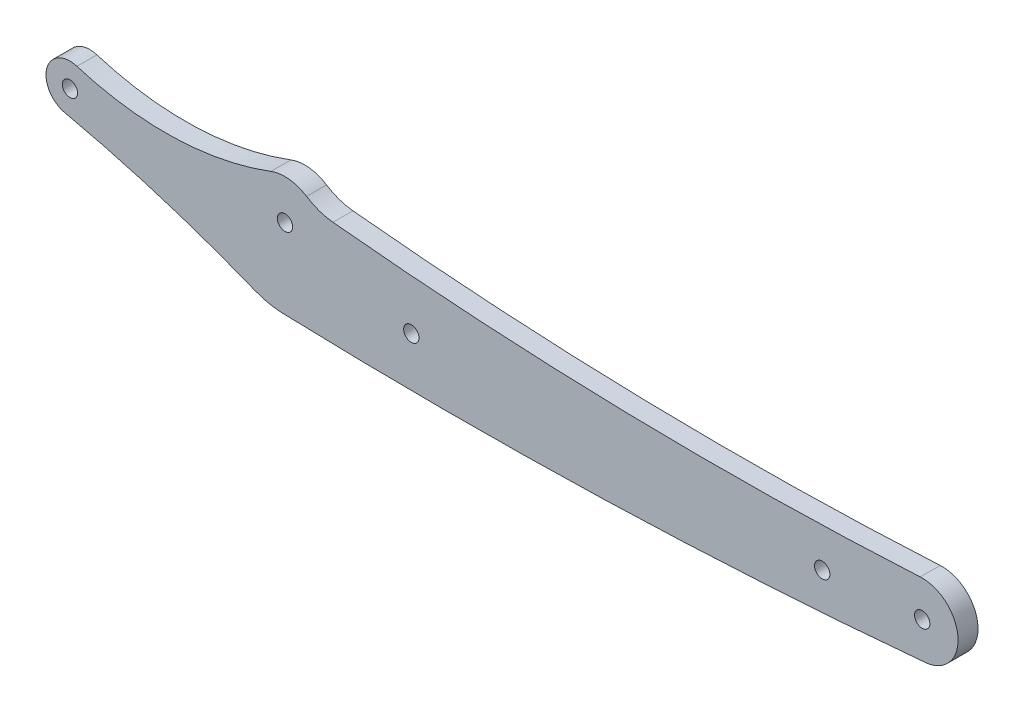
SolidWorks part; units mm, degrees
ref_plane "Plan de face" through (0, 0, 0) normal (0, 0, 1) x (1, 0, 0)
ref_plane "Plan de dessus" through (0, 0, 0) normal (0, 1, 0) x (1, 0, 0)
ref_plane "Plan de droite" through (0, 0, 0) normal (1, 0, 0) x (0, 0, -1)
sketch "Esquisse1" plane through (0, 0, 0) normal (0, 0, 1) x (1, 0, 0)
  arc A0 (-55.8278, -14.4628) -> (105.5259, -9.7214) centre (-13.2616, 1284.8401) ccw
  arc A1 (105.5259, -9.7214) -> (104.2116, 8.2275) centre (104.7036, -0.7591) ccw
  arc A3 (-43.1266, 11.61) -> (104.2116, 8.2275) centre (52.2805, 956.807) ccw
  arc A4 (-49.7518, 13.9295) -> (-58.708, 14.8808) centre (-55.1729, 5.5264) ccw
  arc A5 (-107.3601, 13.3804) -> (-58.708, 14.8808) centre (-85.2207, 85.0383) ccw
  arc A6 (-107.3601, 13.3804) -> (-110.4241, 1.7888) centre (-109.1312, 7.6478) ccw
  arc A7 (-62.6664, -13.0167) -> (-110.4241, 1.7888) centre (-175.0689, -291.1635) ccw
  arc A8 (-62.6664, -13.0167) -> (-55.8278, -14.4628) centre (-55.1729, 5.5264) ccw
  circle A9 centre (-23.4726, -2.7253) radius 1.925
  circle A10 centre (79.6129, -2.5748) radius 1.925
  circle A11 centre (-109.1312, 7.6478) radius 1.925
  circle A12 centre (-55.1729, 5.5264) radius 1.925
  circle A13 centre (104.7036, -0.7591) radius 1.925
  arc A14 (-49.7518, 13.9295) -> (-43.1266, 11.61) centre (-41.6202, 26.5341) ccw
  dimension "D1" = 950
  dimension "D2" = 75
  dimension "D3" = 1300
  dimension "D4" = 300
  dimension "D5" = 15
  dimension "D6" = 10
  dimension "D7" = 6
  dimension "D8" = 20
  dimension "D9" = 9
  dimension "D10" = 3.85
extrude "Boss.-Extru.1" add sketch "Esquisse1" along normal blind 5
